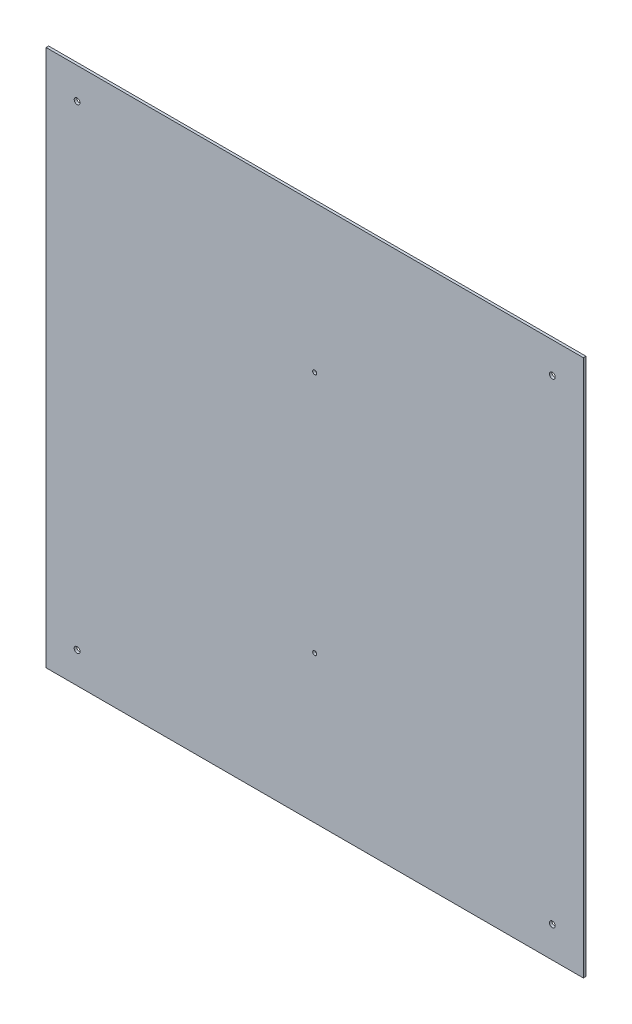
SolidWorks part; units mm, degrees
ref_plane "Front Plane" through (0, 0, 0) normal (0, 0, 1) x (1, 0, 0)
ref_plane "Top Plane" through (0, 0, 0) normal (0, 1, 0) x (1, 0, 0)
ref_plane "Right Plane" through (0, 0, 0) normal (1, 0, 0) x (0, 0, -1)
sketch "Sketch1" plane through (0, 0, 0) normal (0, 0, 1) x (1, 0, 0)
  line L0 (0, 330.2) -> (660.4, 330.2) construction
  line L1 (0, 0) -> (660.4, 0)
  line L2 (0, 0) -> (0, 660.4)
  line L3 (0, 660.4) -> (660.4, 660.4)
  line L4 (660.4, 0) -> (660.4, 660.4)
  line L5 (660.4, 330.2) -> (330.2, 660.4) construction
  line L6 (330.2, 660.4) -> (330.2, 0) construction
  line L7 (330.2, 479.679) -> (330.2, 180.721) construction
  line L8 (38.1, 622.3) -> (38.1, 660.4) construction
  line L9 (38.1, 622.3) -> (0, 622.3) construction
  circle A0 centre (330.2, 479.679) radius 2.5
  circle A1 centre (330.2, 180.721) radius 2.5
  circle A2 centre (38.1, 622.3) radius 3.556
  circle A3 centre (622.3, 622.3) radius 3.556
  circle A4 centre (622.3, 38.1) radius 3.556
  circle A5 centre (38.1, 38.1) radius 3.556
  point P12 (330.2, 330.2)
  dimension "D1" = 5
  dimension "D7" = 7.112
  dimension "D2" = 660.4
  dimension "D3" = 660.4
  dimension "D4" = 298.958
  dimension "D5" = 180.721
  dimension "D6" = 180.721
  dimension "D8" = 38.1
  dimension "D9" = 38.1
  dimension "D10" = 38.1
  dimension "D11" = 38.1
  dimension "D12" = 38.1
  dimension "D13" = 38.1
  dimension "D14" = 38.1
  dimension "D15" = 38.1
extrude "Boss-Extrude1" add sketch "Sketch1" along normal blind 3.175
